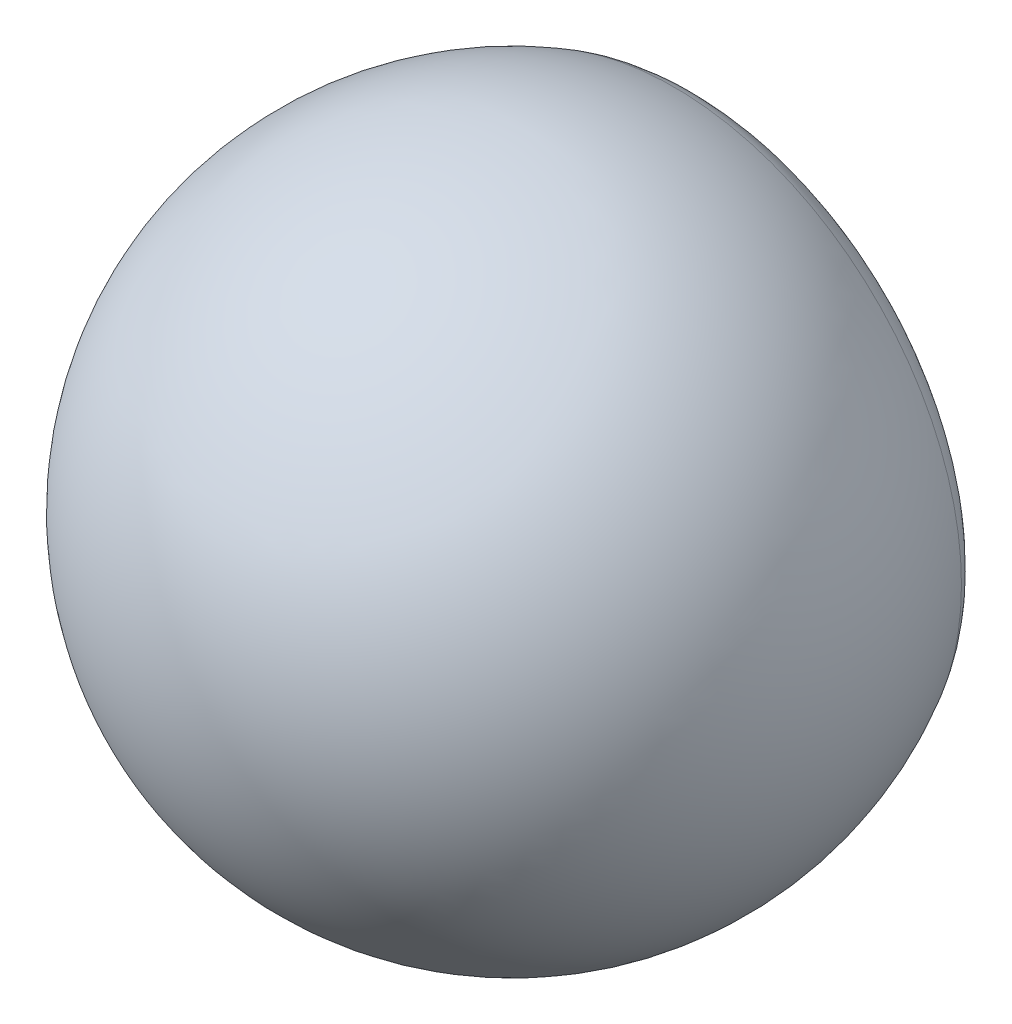
SolidWorks part; units mm, degrees
ref_plane "前视基准面" through (0, 0, 0) normal (0, 0, 1) x (1, 0, 0)
ref_plane "上视基准面" through (0, 0, 0) normal (0, 1, 0) x (1, 0, 0)
ref_plane "右视基准面" through (0, 0, 0) normal (1, 0, 0) x (0, 0, -1)
other "Configuration Table"
sketch "草图2" plane through (0, 0, 0) normal (0, 1, 0) x (1, 0, 0)
  line L0 (0, 0) -> (0, 11.6998) construction
  line L15 (0, -90.962) -> (0, -102.5669)
  arc A21 (4.8496, -87.3944) -> (9.143, -86.9429) centre (7.0937, -88.0943) cw
  arc A22 (4.8496, -87.3944) -> (0, -90.962) centre (0, -85.882) cw
  arc A23 (9.143, -86.9429) -> (0, -102.5669) centre (0, -92.0797) cw
revolve "旋转1" add sketch "草图2" angle 360 about L0
